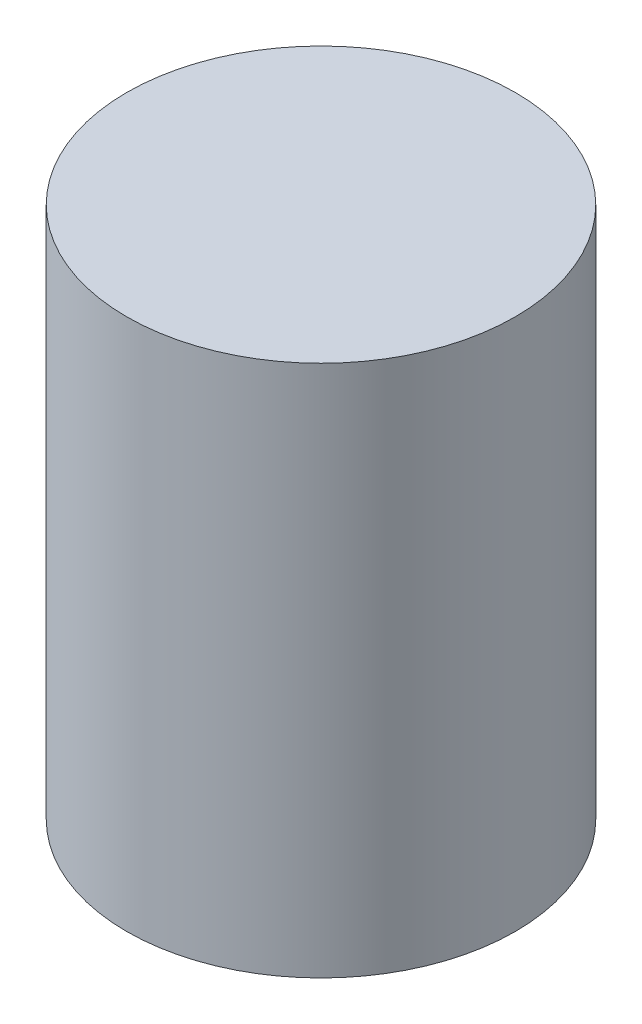
SolidWorks part; units mm, degrees
ref_plane "Front Plane" through (0, 0, 0) normal (0, 0, 1) x (1, 0, 0)
ref_plane "Top Plane" through (0, 0, 0) normal (0, 1, 0) x (1, 0, 0)
ref_plane "Right Plane" through (0, 0, 0) normal (1, 0, 0) x (0, 0, -1)
sketch "Sketch3" plane through (0, 0, 0) normal (0, 1, 0) x (1, 0, 0)
  circle A0 centre (0, 0) radius 1
  dimension "D1" = 2
extrude "Boss-Extrude1" add sketch "Sketch3" along normal blind 2.74
